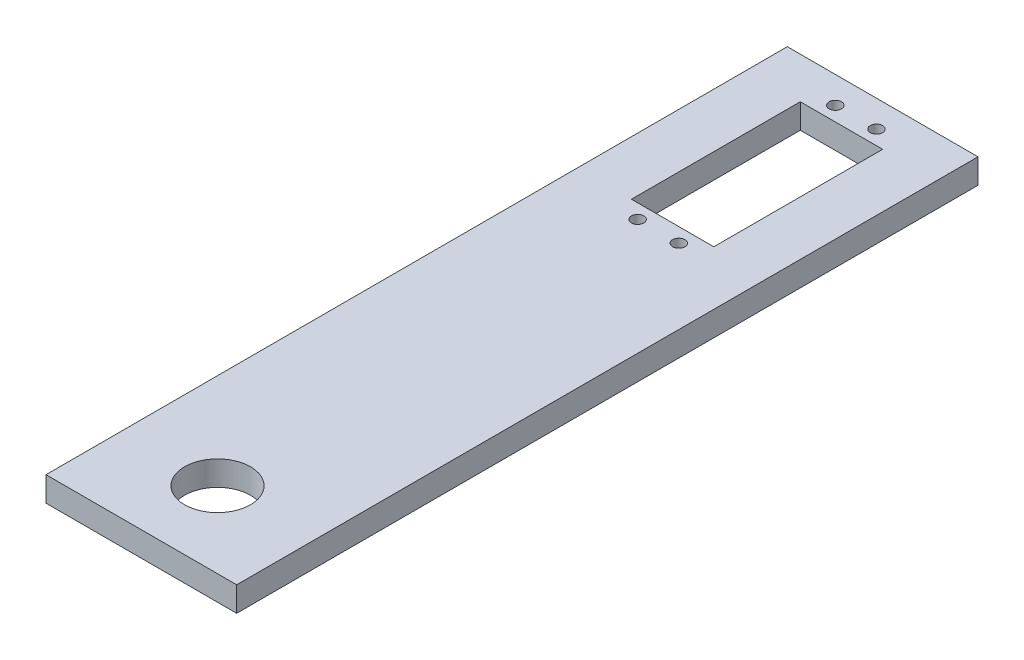
SolidWorks part; units mm, degrees
ref_plane "Front Plane" through (0, 0, 0) normal (0, 0, 1) x (1, 0, 0)
ref_plane "Top Plane" through (0, 0, 0) normal (0, 1, 0) x (1, 0, 0)
ref_plane "Right Plane" through (0, 0, 0) normal (1, 0, 0) x (0, 0, -1)
sketch "Sketch1" plane through (0, 0, 0) normal (0, 1, 0) x (1, 0, 0)
  line L0 (23.15, 180) -> (23.15, 213.5262) construction
  line L1 (0, 0) -> (46.3, 0)
  line L2 (0, 0) -> (0, 180)
  line L3 (0, 180) -> (46.3, 180)
  line L4 (46.3, 0) -> (46.3, 180)
  line L5 (0, 90) -> (46.3, 90) construction
  dimension "D1" = 180
  dimension "D2" = 46.3
extrude "Boss-Extrude1" add sketch "Sketch1" along normal blind 6
sketch "Sketch2" plane through (0, 6, 0) normal (0, 1, 0) x (1, 0, 0)
  line L1 (0, 180) -> (0, 0) construction
  line L2 (0, 0) -> (46.3, 0) construction
  circle A0 centre (23.15, 18.5) radius 8
  dimension "D3" = 16
  dimension "D1" = 18.5
  dimension "D2" = 23.15
extrude "Cut-Extrude1" cut sketch "Sketch2" against normal up to next
sketch "Sketch4" plane through (0, 0, 0) normal (0, -1, 0) x (1, 0, 0)
  line L0 (23.15, -129) -> (23.15, -170) construction
  line L1 (13.15, -129) -> (33.15, -129)
  line L2 (13.15, -129) -> (13.15, -170)
  line L7 (13.15, -170) -> (33.15, -170)
  line L8 (33.15, -129) -> (33.15, -170)
  line L9 (33.15, -149.5) -> (13.15, -149.5) construction
  line L10 (46.3, -180) -> (0, -180) construction
  circle A5 centre (28.15, -173.5) radius 1.5
  circle A6 centre (18.15, -173.5) radius 1.5
  circle A7 centre (18.15, -125.5) radius 1.5
  circle A8 centre (28.15, -125.5) radius 1.5
  circle A9 centre (23.15, -18.5) radius 8 construction
  dimension "D1" = 41
  dimension "D3" = 3
  dimension "D2" = 20
  dimension "D4" = 24
  dimension "D5" = 5
  dimension "D6" = 0
  dimension "D7" = 10
extrude "Cut-Extrude2" cut sketch "Sketch4" against normal up to next
